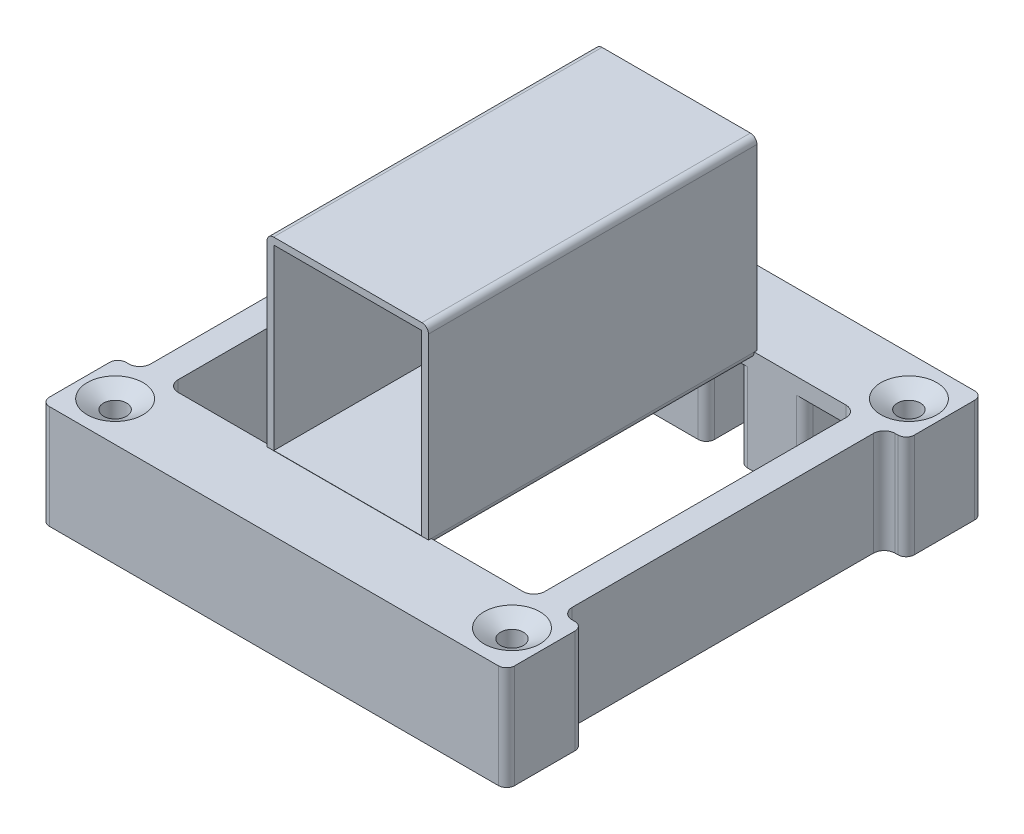
SolidWorks part; units mm, degrees
ref_plane "Front Plane" through (0, 0, 0) normal (0, 0, 1) x (1, 0, 0)
ref_plane "Top Plane" through (0, 0, 0) normal (0, 1, 0) x (1, 0, 0)
ref_plane "Right Plane" through (0, 0, 0) normal (1, 0, 0) x (0, 0, -1)
sketch "Sketch1" plane through (0, 0, 0) normal (0, 0, 1) x (1, 0, 0)
  line L0 (14.75, -16.3) -> (14.75, 16.3) construction
  line L1 (13.55, -17.5) -> (-13.55, -17.5) construction
  line L2 (-14.75, -16.3) -> (-14.75, 16.3) construction
  line L3 (13.55, 17.5) -> (-13.55, 17.5) construction
  line L4 (14.75, -16.3) -> (14.75, 16.3)
  line L5 (13.55, -17.5) -> (-13.55, -17.5)
  line L6 (-14.75, -16.3) -> (-14.75, 16.3)
  line L7 (13.55, 17.5) -> (-13.55, 17.5)
  line L8 (13.5, -16.25) -> (13.5, 16.25) construction
  line L9 (13.5, -16.25) -> (-13.5, -16.25) construction
  line L10 (-13.5, -16.25) -> (-13.5, 16.25) construction
  line L11 (13.5, 16.25) -> (-13.5, 16.25) construction
  line L12 (13.5, -16.25) -> (13.5, 16.25)
  line L13 (13.5, -16.25) -> (-13.5, -16.25)
  line L14 (-13.5, -16.25) -> (-13.5, 16.25)
  line L15 (13.5, 16.25) -> (-13.5, 16.25)
  arc A0 (14.75, 16.3) -> (13.55, 17.5) centre (13.55, 16.3) ccw construction
  arc A1 (13.55, -17.5) -> (14.75, -16.3) centre (13.55, -16.3) ccw construction
  arc A2 (-14.75, -16.3) -> (-13.55, -17.5) centre (-13.55, -16.3) ccw construction
  arc A3 (-13.55, 17.5) -> (-14.75, 16.3) centre (-13.55, 16.3) ccw construction
  arc A4 (14.75, 16.3) -> (13.55, 17.5) centre (13.55, 16.3) ccw
  arc A5 (13.55, -17.5) -> (14.75, -16.3) centre (13.55, -16.3) ccw
  arc A6 (-14.75, -16.3) -> (-13.55, -17.5) centre (-13.55, -16.3) ccw
  arc A7 (-13.55, 17.5) -> (-14.75, 16.3) centre (-13.55, 16.3) ccw
extrude "Boss-Extrude1" add sketch "Sketch1" along normal mid plane 60
sketch "Sketch2" plane through (0, 0, 0) normal (1, 0, 0) x (0, 0, -1)
  line L0 (-29.5, -24.25) -> (-29.5, 24.25) construction
  line L1 (-29.5, -16.3) -> (-43.5, -16.3)
  line L2 (-29.5, -16.3) -> (-29.5, -35.25)
  line L3 (-29.5, -35.25) -> (-43.5, -35.25)
  line L4 (-43.5, -16.3) -> (-43.5, -35.25)
  line L5 (-30, -16.3) -> (30, -16.3) construction
  line L6 (-29.5, -29.25) -> (29.5, -29.25) construction
  line L8 (-43.5, -15.125) -> (-43.5, 15.125) construction
  line L9 (0, 0) -> (0, -45.8115) construction
  line L10 (0, -15.125) -> (0, 15.125) construction
  line L11 (29.5, -35.25) -> (43.5, -35.25)
  line L12 (43.5, -16.3) -> (43.5, -35.25)
  line L13 (29.5, -16.3) -> (43.5, -16.3)
  line L14 (29.5, -16.3) -> (29.5, -35.25)
  dimension "D1" = 6
extrude "Boss-Extrude2" add sketch "Sketch2" along normal mid plane 85
sketch "Sketch3" plane through (0, -35.25, 0) normal (0, -1, 0) x (1, 0, 0)
  line L0 (0, 0) -> (59.8969, 0) construction
  line L1 (42.5, 29.5) -> (-42.5, 29.5) construction
  line L2 (-30, 29.5) -> (-24, 29.5)
  line L3 (-30, 29.5) -> (-30, 39.5)
  line L4 (-30, 39.5) -> (-24, 39.5)
  line L5 (-24, 29.5) -> (-24, 39.5)
  line L6 (-24.25, 29.5) -> (24.25, 29.5) construction
  line L7 (-12, 29.5) -> (-6, 29.5)
  line L8 (-12, 29.5) -> (-12, 39.5)
  line L9 (-12, 39.5) -> (-6, 39.5)
  line L10 (-6, 29.5) -> (-6, 39.5)
  line L11 (0, 0) -> (0, 46.5306) construction
  line L12 (30, 39.5) -> (24, 39.5)
  line L13 (24, 29.5) -> (24, 39.5)
  line L14 (30, 29.5) -> (24, 29.5)
  line L15 (30, 29.5) -> (30, 39.5)
  line L16 (12, 39.5) -> (6, 39.5)
  line L17 (6, 29.5) -> (6, 39.5)
  line L18 (12, 29.5) -> (6, 29.5)
  line L19 (12, 29.5) -> (12, 39.5)
  line L20 (12, -29.5) -> (12, -39.5)
  line L21 (12, -29.5) -> (6, -29.5)
  line L22 (6, -29.5) -> (6, -39.5)
  line L23 (12, -39.5) -> (6, -39.5)
  line L24 (30, -29.5) -> (30, -39.5)
  line L25 (30, -29.5) -> (24, -29.5)
  line L26 (24, -29.5) -> (24, -39.5)
  line L27 (30, -39.5) -> (24, -39.5)
  line L28 (-6, -29.5) -> (-6, -39.5)
  line L29 (-12, -39.5) -> (-6, -39.5)
  line L30 (-12, -29.5) -> (-12, -39.5)
  line L31 (-12, -29.5) -> (-6, -29.5)
  line L32 (-24, -29.5) -> (-24, -39.5)
  line L33 (-30, -39.5) -> (-24, -39.5)
  line L34 (-30, -29.5) -> (-30, -39.5)
  line L35 (-30, -29.5) -> (-24, -29.5)
  dimension "D1" = 12
  dimension "D2" = 12
  dimension "D3" = 6
  dimension "D4" = 6
  dimension "D5" = 10
extrude "Cut-Extrude1" cut sketch "Sketch3" against normal blind 16
fillet "Fillet1" radius 1.49 40 edges at (-24, -27.25, -39.5) (-6, -27.25, -39.5) (12, -27.25, -39.5) (30, -27.25, -39.5) (42.5, -25.775, -29.5) (42.5, -25.775, -43.5) (-42.5, -25.775, -43.5) (-42.5, -25.775, -29.5) (-30, -27.25, -29.5) (-30, -27.25, -39.5) (-24, -27.25, -29.5) (-12, -27.25, -29.5) (-12, -27.25, -39.5) (-6, -27.25, -29.5) (6, -27.25, -29.5) (6, -27.25, -39.5) (12, -27.25, -29.5) (24, -27.25, -29.5) (24, -27.25, -39.5) (30, -27.25, -29.5) (24, -27.25, 39.5) (6, -27.25, 39.5) (-12, -27.25, 39.5) (-30, -27.25, 39.5) (42.5, -25.775, 43.5) (42.5, -25.775, 29.5) (30, -27.25, 29.5) (30, -27.25, 39.5) (24, -27.25, 29.5) (12, -27.25, 29.5) (12, -27.25, 39.5) (6, -27.25, 29.5) (-6, -27.25, 29.5) (-6, -27.25, 39.5) (-12, -27.25, 29.5) (-24, -27.25, 29.5) (-24, -27.25, 39.5) (-30, -27.25, 29.5) (-42.5, -25.775, 43.5) (-42.5, -25.775, 29.5)
sketch "Sketch4" plane through (0, -16.3, 0) normal (0, 1, 0) x (1, 0, 0)
  line L0 (0, 0) -> (38.8928, 0) construction
  line L1 (-36.25, 36.25) -> (36.25, 36.25) construction
  line L2 (-36.25, 36.25) -> (-36.25, -36.25) construction
  line L3 (-36.25, -36.25) -> (36.25, -36.25) construction
  line L4 (36.25, 36.25) -> (36.25, -36.25) construction
  line L5 (-36.25, 36.25) -> (36.25, -36.25) construction
  line L6 (-36.25, -36.25) -> (36.25, 36.25) construction
  line L7 (0, 0) -> (0, -47.3346) construction
  circle A0 centre (36.25, -36.25) radius 2.1
  circle A1 centre (-36.25, -36.25) radius 2.1
  circle A2 centre (-36.25, 36.25) radius 2.1
  circle A3 centre (36.25, 36.25) radius 2.1
  point P0 (0, 0)
  dimension "D3" = 4.2
  dimension "D1" = 72.5
  dimension "D2" = 72.5
extrude "Cut-Extrude2" cut sketch "Sketch4" against normal through all both and the other way through all
chamfer "Chamfer1" distance 3 angle 30 4 edges at (36.25, -16.3, -38.35) (-36.25, -16.3, -38.35) (-36.25, -16.3, 34.15) (36.25, -16.3, 34.15)
sketch "Sketch5" plane through (0, 0, -29.5) normal (0, 0, 1) x (1, 0, 0)
  line L0 (-14.75, -16.3) -> (-41.01, -16.3) construction
  line L1 (-38.5, -16.3) -> (-33.5, -16.3)
  line L2 (-38.5, -16.3) -> (-38.5, -35.25)
  line L3 (-38.5, -35.25) -> (-33.5, -35.25)
  line L4 (-33.5, -16.3) -> (-33.5, -35.25)
  line L5 (-31.49, -35.25) -> (-41.01, -35.25) construction
  line L6 (-42.5, -35.25) -> (-42.5, -16.3) construction
  line L7 (0, 0) -> (0, -37.6996) construction
  line L8 (33.5, -16.3) -> (33.5, -35.25)
  line L9 (38.5, -35.25) -> (33.5, -35.25)
  line L10 (38.5, -16.3) -> (38.5, -35.25)
  line L11 (38.5, -16.3) -> (33.5, -16.3)
  dimension "D1" = 4
  dimension "D2" = 5
extrude "Boss-Extrude3" add sketch "Sketch5" along normal up to surface (59 mm away) up to face at (0, -25.2999, 29.5)
fillet "Fillet2" radius 2 8 edges at (33.5, -25.775, 29.5) (38.5, -25.775, 29.5) (33.5, -25.775, -29.5) (38.5, -25.775, -29.5) (-38.5, -25.775, -29.5) (-33.5, -25.775, -29.5) (-33.5, -25.775, 29.5) (-38.5, -25.775, 29.5)
